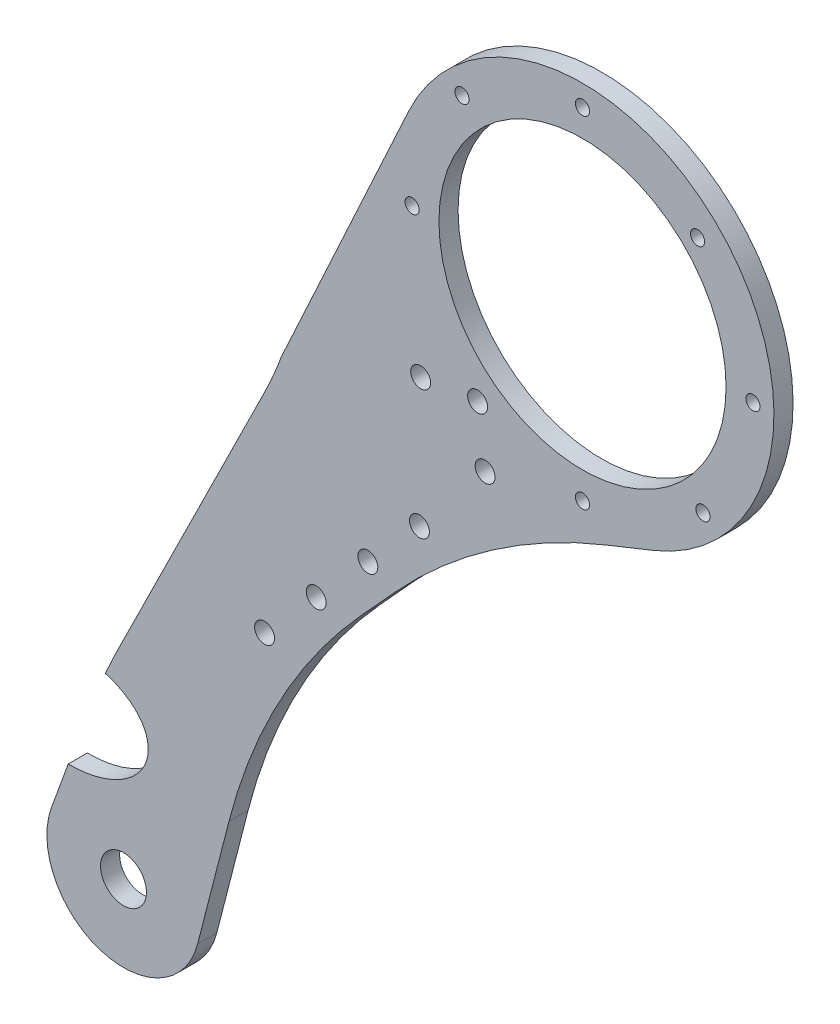
SolidWorks part; units mm, degrees
ref_plane "前视基准面" through (0, 0, 0) normal (0, 0, 1) x (1, 0, 0)
ref_plane "上视基准面" through (0, 0, 0) normal (0, 1, 0) x (1, 0, 0)
ref_plane "右视基准面" through (0, 0, 0) normal (1, 0, 0) x (0, 0, -1)
other "Configuration Table"
sketch "草图2" plane through (0, 0, 0) normal (0, 0, 1) x (1, 0, 0)
  line L3 (46.1569, 11.7262) -> (53.8034, 15.2249)
  line L4 (-24.1039, 62.5864) -> (-38.1759, 23.9239)
  line L5 (-42.531, 13.749) -> (-80.4781, -62.8808)
  line L6 (-93.8568, -96.0567) -> (-98.223, -108.0528)
  line L7 (-61.0282, -122.7294) -> (-40.8494, -75.3454)
  circle A0 centre (84.9497, 75.0973) radius 1.85
  circle A1 centre (-4.0503, 75.0973) radius 1.85
  circle A2 centre (71.916, 43.6311) radius 1.85
  circle A3 centre (-79.4291, -114.8932) radius 6
  circle A5 centre (40.4497, 30.5973) radius 1.85
  circle A7 centre (8.9835, 106.5636) radius 1.85
  circle A8 centre (40.4497, 119.5973) radius 1.85
  circle A9 centre (91.2631, 96.1449) radius 2.6
  circle A10 centre (61.4973, 125.9107) radius 2.6
  circle A11 centre (19.4021, 125.9107) radius 2.6
  circle A12 centre (-10.3636, 96.1449) radius 2.6
  circle A15 centre (61.4973, 24.284) radius 2.6
  circle A16 centre (91.2631, 54.0497) radius 2.6
  circle A21 centre (40.4497, 75.0973) radius 40
  arc A25 (-16.723, -33.5512) -> (-40.8494, -75.3454) centre (143.16, -153.707) ccw
  arc A26 (46.1569, 11.7262) -> (-16.723, -33.5512) centre (129.3708, -170.1403) ccw
  arc A27 (62.9573, 19.4789) -> (53.8034, 15.2249) centre (100.47, -73.2184) ccw
  arc A28 (62.9573, 19.4789) -> (-18.9963, 83.2315) centre (40.4497, 75.0973) ccw
  arc A29 (-24.1039, 62.5864) -> (-18.9963, 83.2315) centre (-118.0731, 96.7885) ccw
  arc A30 (-42.531, 13.749) -> (-38.1759, 23.9239) centre (-132.1451, 58.1259) ccw
  arc A31 (-80.4781, -62.8808) -> (-84.1514, -70.7209) centre (98.7501, -151.6347) ccw
  arc A32 (-98.223, -108.0528) -> (-61.0282, -122.7294) centre (-79.4291, -114.8932) ccw
  ellipse E0 centre (-92.5686, -82.8702) end of major axis (-112.1659, -83.9215) minor radius 13.1666 (-93.8568, -96.0567) -> (-84.1514, -70.7209) ccw
extrude "凸台-拉伸1" add sketch "草图2" along normal blind 5
sketch "草图4" plane through (0, 0, 5) normal (0, 0, 1) x (1, 0, 0)
  line L0 (40.4497, 75.0973) -> (13.0555, 39.3964)
  line L1 (40.4497, 75.0973) -> (40.4497, 119.5973)
  line L2 (40.4497, 75.0973) -> (13.5399, 40.0277)
  line L3 (24.9558, 30.265) -> (13.0555, 39.3964)
  line L4 (15.0134, 24.5248) -> (-1.8162, 37.4385)
  line L5 (46.1569, 11.7262) -> (53.8034, 15.2249)
  line L6 (-24.1039, 62.5864) -> (-38.1759, 23.9239)
  line L7 (-42.531, 13.749) -> (-80.4781, -62.8808)
  line L8 (-93.8568, -96.0567) -> (-98.223, -108.0528)
  line L9 (-61.0282, -122.7294) -> (-40.8494, -75.3454)
  line L10 (46.1569, 11.7262) -> (53.8034, 15.2249)
  line L11 (-24.1039, 62.5864) -> (-38.1759, 23.9239)
  line L12 (-42.531, 13.749) -> (-80.4781, -62.8808)
  line L13 (-93.8568, -96.0567) -> (-98.223, -108.0528)
  line L14 (-61.0282, -122.7294) -> (-40.8494, -75.3454)
  circle A0 centre (13.0555, 39.3964) radius 15
  circle A5 centre (15.0134, 24.5248) radius 2.6
  circle A6 centre (-1.8162, 37.4385) radius 2.6
  circle A7 centre (11.0976, 54.2681) radius 2.6
  arc A8 (46.1569, 11.7262) -> (-16.723, -33.5512) centre (129.3708, -170.1403) ccw
  arc A9 (62.9573, 19.4789) -> (53.8034, 15.2249) centre (100.47, -73.2184) ccw
  arc A10 (62.9573, 19.4789) -> (-18.9963, 83.2315) centre (40.4497, 75.0973) ccw
  arc A11 (-24.1039, 62.5864) -> (-18.9963, 83.2315) centre (-118.0731, 96.7885) ccw
  arc A12 (-42.531, 13.749) -> (-38.1759, 23.9239) centre (-132.1451, 58.1259) ccw
  arc A13 (-80.4781, -62.8808) -> (-84.1514, -70.7209) centre (98.7501, -151.6347) ccw
  arc A14 (-98.223, -108.0528) -> (-61.0282, -122.7294) centre (-79.4291, -114.8932) ccw
  arc A15 (-16.723, -33.5512) -> (-40.8494, -75.3454) centre (143.16, -153.707) ccw
  arc A16 (46.1569, 11.7262) -> (-16.723, -33.5512) centre (129.3708, -170.1403) ccw
  arc A17 (62.9573, 19.4789) -> (53.8034, 15.2249) centre (100.47, -73.2184) ccw
  arc A18 (62.9573, 19.4789) -> (-18.9963, 83.2315) centre (40.4497, 75.0973) ccw
  arc A19 (-24.1039, 62.5864) -> (-18.9963, 83.2315) centre (-118.0731, 96.7885) ccw
  arc A20 (-42.531, 13.749) -> (-38.1759, 23.9239) centre (-132.1451, 58.1259) ccw
  arc A21 (-80.4781, -62.8808) -> (-84.1514, -70.7209) centre (98.7501, -151.6347) ccw
  arc A22 (-98.223, -108.0528) -> (-61.0282, -122.7294) centre (-79.4291, -114.8932) ccw
  arc A23 (-16.723, -33.5512) -> (-40.8494, -75.3454) centre (143.16, -153.707) ccw
  circle A24 centre (27.9271, 41.3543) radius 2.6
  ellipse E1 centre (-92.5686, -82.8702) end of major axis (-72.9713, -81.819) minor radius 13.1666 (-93.8568, -96.0567) -> (-84.1514, -70.7209) ccw
  ellipse E2 centre (-92.5686, -82.8702) end of major axis (-72.9713, -81.819) minor radius 13.1666 (-93.8568, -96.0567) -> (-84.1514, -70.7209) ccw
  point P47 (13.0555, 39.3964)
  dimension "D3" = 30
  dimension "D4" = 4
  dimension "D5" = 5.2
  dimension "D6" = 142.5
  dimension "D2" = 45
  dimension "D1" = 0
extrude "切除-拉伸3" cut sketch "草图4" against normal through all contours L4 A6 A0 | A0 A6 | A0 A6 L4 | L4 A5 A0 | A0 A5 L4 | A0 A5
sketch "草图5" plane through (0, 0, 5) normal (0, 0, 1) x (1, 0, 0)
  line L0 (-8.4235, 16.054) -> (-20.1211, 24.5355)
  line L1 (-27.5368, 22.7065) -> (-60.0257, -42.901)
  line L2 (-56.7563, -45.137) -> (-7.6659, 8.6349)
  line L3 (-42.531, 13.749) -> (-80.4781, -62.8808) construction
  arc A0 (-7.6659, 8.6349) -> (-8.4235, 16.054) centre (-11.3585, 12.0061) ccw
  arc A1 (-27.5368, 22.7065) -> (-20.1211, 24.5355) centre (-23.0561, 20.4876) cw
  arc A2 (-60.0257, -42.901) -> (-56.7563, -45.137) centre (-58.2334, -43.7886) ccw
  dimension "D1" = 5
  dimension "D2" = 2
extrude "切除-拉伸4" cut sketch "草图5" against normal blind 10 contours L2 A0 L0 A1 L1 A2
sketch "草图6" plane through (0, 0, 5) normal (0, 0, 1) x (1, 0, 0)
  line L0 (40.4497, 75.0973) -> (40.4497, 119.5973)
  line L1 (40.4497, 75.0973) -> (70.5018, 105.1494)
  line L2 (40.4497, 75.0973) -> (10.3977, 45.0453)
  circle A0 centre (70.5018, 105.1494) radius 1.85
  circle A2 centre (40.4497, 75.0973) radius 40 construction
  circle A3 centre (40.4497, 75.0973) radius 40
  circle A4 centre (40.4497, 75.0973) radius 42.5
  circle A5 centre (10.3977, 45.0453) radius 1.85
  dimension "D1" = 85
  dimension "D2" = 3.7
  dimension "D4" = 3.7
  dimension "D3" = 45
extrude "切除-拉伸5" cut sketch "草图6" against normal blind 10 contours A4 A0 | A0 A4 L1 | L1 A4 A0
sketch "草图7" plane through (0, 0, 5) normal (0, 0, 1) x (1, 0, 0)
  line L0 (-38.1759, 23.9239) -> (-4.9629, 96.0183)
  line L1 (12.5033, -7.8382) -> (70.2161, 34.9232)
  line L5 (46.1569, 11.7262) -> (53.8034, 15.2249)
  line L6 (-24.1039, 62.5864) -> (-38.1759, 23.9239)
  line L7 (-42.531, 13.749) -> (-80.4781, -62.8808)
  line L8 (-93.8568, -96.0567) -> (-98.223, -108.0528)
  line L9 (-61.0282, -122.7294) -> (-40.8494, -75.3454)
  line L10 (46.1569, 11.7262) -> (53.8034, 15.2249)
  line L11 (-24.1039, 62.5864) -> (-38.1759, 23.9239)
  line L12 (-42.531, 13.749) -> (-80.4781, -62.8808)
  line L13 (-93.8568, -96.0567) -> (-98.223, -108.0528)
  line L14 (-61.0282, -122.7294) -> (-40.8494, -75.3454)
  circle A0 centre (40.4497, 75.0973) radius 40 construction
  circle A1 centre (40.4497, 75.0973) radius 40
  circle A2 centre (40.4497, 75.0973) radius 50
  arc A11 (46.1569, 11.7262) -> (-16.723, -33.5512) centre (129.3708, -170.1403) ccw
  arc A12 (62.9573, 19.4789) -> (53.8034, 15.2249) centre (100.47, -73.2184) ccw
  arc A13 (62.9573, 19.4789) -> (-18.9963, 83.2315) centre (40.4497, 75.0973) ccw
  arc A14 (-24.1039, 62.5864) -> (-18.9963, 83.2315) centre (-118.0731, 96.7885) ccw
  arc A15 (-42.531, 13.749) -> (-38.1759, 23.9239) centre (-132.1451, 58.1259) ccw
  arc A16 (-80.4781, -62.8808) -> (-84.1514, -70.7209) centre (98.7501, -151.6347) ccw
  arc A17 (-98.223, -108.0528) -> (-61.0282, -122.7294) centre (-79.4291, -114.8932) ccw
  arc A18 (-16.723, -33.5512) -> (-40.8494, -75.3454) centre (143.16, -153.707) ccw
  arc A19 (46.1569, 11.7262) -> (-16.723, -33.5512) centre (129.3708, -170.1403) ccw
  arc A20 (62.9573, 19.4789) -> (53.8034, 15.2249) centre (100.47, -73.2184) ccw
  arc A21 (62.9573, 19.4789) -> (-18.9963, 83.2315) centre (40.4497, 75.0973) ccw
  arc A22 (-24.1039, 62.5864) -> (-18.9963, 83.2315) centre (-118.0731, 96.7885) ccw
  arc A23 (-42.531, 13.749) -> (-38.1759, 23.9239) centre (-132.1451, 58.1259) ccw
  arc A24 (-80.4781, -62.8808) -> (-84.1514, -70.7209) centre (98.7501, -151.6347) ccw
  arc A25 (-98.223, -108.0528) -> (-61.0282, -122.7294) centre (-79.4291, -114.8932) ccw
  arc A26 (-16.723, -33.5512) -> (-40.8494, -75.3454) centre (143.16, -153.707) ccw
  ellipse E1 centre (-92.5686, -82.8702) end of major axis (-72.9713, -81.819) minor radius 13.1666 (-93.8568, -96.0567) -> (-84.1514, -70.7209) ccw
  ellipse E2 centre (-92.5686, -82.8702) end of major axis (-72.9713, -81.819) minor radius 13.1666 (-93.8568, -96.0567) -> (-84.1514, -70.7209) ccw
  circle M12 centre (91.2631, 54.0497) radius 2.6
  circle M14 centre (19.4021, 125.9107) radius 2.6
  circle M15 centre (91.2631, 96.1449) radius 2.6
  arc M19 (-16.723, -33.5512) -> (46.1569, 11.7262) centre (129.3708, -170.1403) cw
  line M20 (46.1569, 11.7262) -> (53.8034, 15.2249)
  arc M21 (53.8034, 15.2249) -> (62.9573, 19.4789) centre (100.47, -73.2184) cw
  arc M22 (62.9573, 19.4789) -> (-18.9963, 83.2315) centre (40.4497, 75.0973) ccw
  arc M23 (-18.9963, 83.2315) -> (-24.1039, 62.5864) centre (-118.0731, 96.7885) cw
  line M24 (-24.1039, 62.5864) -> (-38.1759, 23.9239)
  circle M37 centre (61.4973, 125.9107) radius 2.6
  circle M38 centre (-10.3636, 96.1449) radius 2.6
  circle M39 centre (61.4973, 24.284) radius 2.6
  dimension "D1" = 100
  dimension "D2" = 0
extrude "切除-拉伸6" cut sketch "草图7" against normal blind 10 contours A2 L1 L0 M19 M20 M21 M22 M23 M24 M12 M14 M37 M39 M38 M15
sketch "草图8" plane through (0, 0, 5) normal (0, 0, 1) x (1, 0, 0)
  line L3 (-27.5368, 22.7065) -> (-60.0257, -42.901)
  line L4 (-8.4235, 16.054) -> (-20.1211, 24.5355)
  line L5 (-56.7563, -45.137) -> (-7.6659, 8.6349)
  line L6 (-27.5368, 22.7065) -> (-60.0257, -42.901)
  line L7 (-8.4235, 16.054) -> (-20.1211, 24.5355)
  line L8 (-56.7563, -45.137) -> (-7.6659, 8.6349)
  line L11 (-4.9629, 96.0183) -> (-38.1759, 23.9239)
  line L12 (-42.531, 13.749) -> (-80.4781, -62.8808)
  line L13 (-93.8568, -96.0567) -> (-98.223, -108.0528)
  line L14 (-61.0282, -122.7294) -> (-40.8494, -75.3454)
  line L15 (12.5033, -7.8382) -> (70.2161, 34.9232)
  line L16 (-4.9629, 96.0183) -> (-38.1759, 23.9239)
  line L17 (-42.531, 13.749) -> (-80.4781, -62.8808)
  line L18 (-93.8568, -96.0567) -> (-98.223, -108.0528)
  line L19 (-61.0282, -122.7294) -> (-40.8494, -75.3454)
  line L20 (12.5033, -7.8382) -> (70.2161, 34.9232)
  circle A1 centre (84.9497, 75.0973) radius 1.85
  circle A2 centre (84.9497, 75.0973) radius 1.85
  circle A3 centre (-4.0503, 75.0973) radius 1.85
  circle A4 centre (-4.0503, 75.0973) radius 1.85
  circle A5 centre (71.916, 43.6311) radius 1.85
  circle A6 centre (71.916, 43.6311) radius 1.85
  circle A7 centre (-79.4291, -114.8932) radius 6
  circle A8 centre (-79.4291, -114.8932) radius 6
  circle A9 centre (40.4497, 30.5973) radius 1.85
  circle A10 centre (40.4497, 30.5973) radius 1.85
  circle A11 centre (8.9835, 106.5636) radius 1.85
  circle A12 centre (8.9835, 106.5636) radius 1.85
  circle A13 centre (40.4497, 119.5973) radius 1.85
  circle A14 centre (40.4497, 119.5973) radius 1.85
  circle A25 centre (40.4497, 75.0973) radius 40
  circle A26 centre (40.4497, 75.0973) radius 40
  circle A27 centre (15.0134, 24.5248) radius 2.6
  circle A28 centre (15.0134, 24.5248) radius 2.6
  circle A29 centre (-1.8162, 37.4385) radius 2.6
  circle A30 centre (-1.8162, 37.4385) radius 2.6
  circle A31 centre (70.5018, 105.1494) radius 1.85
  circle A32 centre (70.5018, 105.1494) radius 1.85
  arc A33 (-60.0257, -42.901) -> (-56.7563, -45.137) centre (-58.2334, -43.7886) ccw
  arc A34 (-20.1211, 24.5355) -> (-27.5368, 22.7065) centre (-23.0561, 20.4876) ccw
  arc A35 (-7.6659, 8.6349) -> (-8.4235, 16.054) centre (-11.3585, 12.0061) ccw
  arc A36 (-60.0257, -42.901) -> (-56.7563, -45.137) centre (-58.2334, -43.7886) ccw
  arc A37 (-20.1211, 24.5355) -> (-27.5368, 22.7065) centre (-23.0561, 20.4876) ccw
  arc A38 (-7.6659, 8.6349) -> (-8.4235, 16.054) centre (-11.3585, 12.0061) ccw
  arc A44 (-42.531, 13.749) -> (-38.1759, 23.9239) centre (-132.1451, 58.1259) ccw
  arc A45 (-80.4781, -62.8808) -> (-84.1514, -70.7209) centre (98.7501, -151.6347) ccw
  arc A46 (-98.223, -108.0528) -> (-61.0282, -122.7294) centre (-79.4291, -114.8932) ccw
  arc A47 (-16.723, -33.5512) -> (-40.8494, -75.3454) centre (143.16, -153.707) ccw
  arc A48 (12.5033, -7.8382) -> (-16.723, -33.5512) centre (129.3708, -170.1403) ccw
  arc A49 (70.2161, 34.9232) -> (-4.9629, 96.0183) centre (40.4497, 75.0973) ccw
  arc A50 (-42.531, 13.749) -> (-38.1759, 23.9239) centre (-132.1451, 58.1259) ccw
  arc A51 (-80.4781, -62.8808) -> (-84.1514, -70.7209) centre (98.7501, -151.6347) ccw
  arc A52 (-98.223, -108.0528) -> (-61.0282, -122.7294) centre (-79.4291, -114.8932) ccw
  arc A53 (-16.723, -33.5512) -> (-40.8494, -75.3454) centre (143.16, -153.707) ccw
  arc A54 (12.5033, -7.8382) -> (-16.723, -33.5512) centre (129.3708, -170.1403) ccw
  arc A55 (70.2161, 34.9232) -> (-4.9629, 96.0183) centre (40.4497, 75.0973) ccw
  ellipse E1 centre (-92.5686, -82.8702) end of major axis (-72.9713, -81.819) minor radius 13.1666 (-93.8568, -96.0567) -> (-84.1514, -70.7209) ccw
  ellipse E2 centre (-92.5686, -82.8702) end of major axis (-72.9713, -81.819) minor radius 13.1666 (-93.8568, -96.0567) -> (-84.1514, -70.7209) ccw
  dimension "D1" = 0
  dimension "D2" = 0
  dimension "D3" = 0
  dimension "D4" = 0
  dimension "D5" = 0
  dimension "D6" = 0
  dimension "D7" = 0
  dimension "D13" = 0
  dimension "D14" = 0
  dimension "D15" = 0
  dimension "D16" = 0
  dimension "D17" = 0
  dimension "D18" = 0
sketch "草图9" plane through (0, 0, 5) normal (0, 0, 1) x (1, 0, 0)
  circle A0 centre (40.4497, 75.0973) radius 35
  circle A1 centre (40.4497, 75.0973) radius 40 construction
  circle A2 centre (40.4497, 75.0973) radius 40
  dimension "D1" = 5
extrude "凸台-拉伸2" add sketch "草图9" against normal blind 5
sketch "草图10" plane through (0, 0, 5) normal (0, 0, 1) x (1, 0, 0)
  line L3 (-27.5368, 22.7065) -> (-60.0257, -42.901)
  line L4 (-8.4235, 16.054) -> (-20.1211, 24.5355)
  line L5 (-56.7563, -45.137) -> (-7.6659, 8.6349)
  line L6 (-27.5368, 22.7065) -> (-60.0257, -42.901)
  line L7 (-8.4235, 16.054) -> (-20.1211, 24.5355)
  line L8 (-56.7563, -45.137) -> (-7.6659, 8.6349)
  line L11 (-4.9629, 96.0183) -> (-38.1759, 23.9239)
  line L12 (-42.531, 13.749) -> (-80.4781, -62.8808)
  line L13 (-93.8568, -96.0567) -> (-98.223, -108.0528)
  line L14 (-61.0282, -122.7294) -> (-40.8494, -75.3454)
  line L15 (12.5033, -7.8382) -> (70.2161, 34.9232)
  line L16 (-4.9629, 96.0183) -> (-38.1759, 23.9239)
  line L17 (-42.531, 13.749) -> (-80.4781, -62.8808)
  line L18 (-93.8568, -96.0567) -> (-98.223, -108.0528)
  line L19 (-61.0282, -122.7294) -> (-40.8494, -75.3454)
  line L20 (12.5033, -7.8382) -> (70.2161, 34.9232)
  circle A0 centre (40.4497, 75.0973) radius 37.5
  circle A1 centre (84.9497, 75.0973) radius 1.85
  circle A2 centre (84.9497, 75.0973) radius 1.85
  circle A3 centre (-4.0503, 75.0973) radius 1.85
  circle A4 centre (-4.0503, 75.0973) radius 1.85
  circle A5 centre (71.916, 43.6311) radius 1.85
  circle A6 centre (71.916, 43.6311) radius 1.85
  circle A7 centre (-79.4291, -114.8932) radius 6
  circle A8 centre (-79.4291, -114.8932) radius 6
  circle A9 centre (40.4497, 30.5973) radius 1.85
  circle A10 centre (40.4497, 30.5973) radius 1.85
  circle A11 centre (8.9835, 106.5636) radius 1.85
  circle A12 centre (8.9835, 106.5636) radius 1.85
  circle A13 centre (40.4497, 119.5973) radius 1.85
  circle A14 centre (40.4497, 119.5973) radius 1.85
  circle A25 centre (15.0134, 24.5248) radius 2.6
  circle A26 centre (15.0134, 24.5248) radius 2.6
  circle A27 centre (-1.8162, 37.4385) radius 2.6
  circle A28 centre (-1.8162, 37.4385) radius 2.6
  circle A29 centre (70.5018, 105.1494) radius 1.85
  circle A30 centre (70.5018, 105.1494) radius 1.85
  arc A31 (-60.0257, -42.901) -> (-56.7563, -45.137) centre (-58.2334, -43.7886) ccw
  arc A32 (-20.1211, 24.5355) -> (-27.5368, 22.7065) centre (-23.0561, 20.4876) ccw
  arc A33 (-7.6659, 8.6349) -> (-8.4235, 16.054) centre (-11.3585, 12.0061) ccw
  arc A34 (-60.0257, -42.901) -> (-56.7563, -45.137) centre (-58.2334, -43.7886) ccw
  arc A35 (-20.1211, 24.5355) -> (-27.5368, 22.7065) centre (-23.0561, 20.4876) ccw
  arc A36 (-7.6659, 8.6349) -> (-8.4235, 16.054) centre (-11.3585, 12.0061) ccw
  circle A37 centre (40.4497, 75.0973) radius 35
  circle A38 centre (40.4497, 75.0973) radius 35
  arc A44 (-42.531, 13.749) -> (-38.1759, 23.9239) centre (-132.1451, 58.1259) ccw
  arc A45 (-80.4781, -62.8808) -> (-84.1514, -70.7209) centre (98.7501, -151.6347) ccw
  arc A46 (-98.223, -108.0528) -> (-61.0282, -122.7294) centre (-79.4291, -114.8932) ccw
  arc A47 (-16.723, -33.5512) -> (-40.8494, -75.3454) centre (143.16, -153.707) ccw
  arc A48 (12.5033, -7.8382) -> (-16.723, -33.5512) centre (129.3708, -170.1403) ccw
  arc A49 (70.2161, 34.9232) -> (-4.9629, 96.0183) centre (40.4497, 75.0973) ccw
  arc A50 (-42.531, 13.749) -> (-38.1759, 23.9239) centre (-132.1451, 58.1259) ccw
  arc A51 (-80.4781, -62.8808) -> (-84.1514, -70.7209) centre (98.7501, -151.6347) ccw
  arc A52 (-98.223, -108.0528) -> (-61.0282, -122.7294) centre (-79.4291, -114.8932) ccw
  arc A53 (-16.723, -33.5512) -> (-40.8494, -75.3454) centre (143.16, -153.707) ccw
  arc A54 (12.5033, -7.8382) -> (-16.723, -33.5512) centre (129.3708, -170.1403) ccw
  arc A55 (70.2161, 34.9232) -> (-4.9629, 96.0183) centre (40.4497, 75.0973) ccw
  ellipse E1 centre (-92.5686, -82.8702) end of major axis (-72.9713, -81.819) minor radius 13.1666 (-93.8568, -96.0567) -> (-84.1514, -70.7209) ccw
  ellipse E2 centre (-92.5686, -82.8702) end of major axis (-72.9713, -81.819) minor radius 13.1666 (-93.8568, -96.0567) -> (-84.1514, -70.7209) ccw
  circle M68 centre (40.4497, 75.0973) radius 35
  dimension "D19" = 75
  dimension "D1" = 0
  dimension "D2" = 0
  dimension "D3" = 0
  dimension "D4" = 0
  dimension "D5" = 0
  dimension "D6" = 0
  dimension "D7" = 0
  dimension "D13" = 0
  dimension "D14" = 0
  dimension "D15" = 0
  dimension "D16" = 0
  dimension "D17" = 0
  dimension "D18" = 0
extrude "切除-拉伸7" cut sketch "草图10" against normal blind 6 contours A0 M68
sketch "草图11" plane through (0, 0, 5) normal (0, 0, 1) x (1, 0, 0)
  line L0 (-56.7563, -45.137) -> (-7.6659, 8.6349) construction
  line L1 (-56.7563, -45.137) -> (-7.6659, 8.6349)
  line L2 (-51.2174, -50.1937) -> (-2.1269, 3.5782)
  circle A0 centre (-2.1269, 3.5782) radius 2.6
  circle A1 centre (-15.6115, -11.1923) radius 2.6
  circle A2 centre (-29.096, -25.9627) radius 2.6
  circle A3 centre (-42.5806, -40.7332) radius 2.6
  dimension "D2" = 5.2
  dimension "D4" = 20
  dimension "D1" = 7.5
  dimension "D3" = 4
extrude "切除-拉伸8" cut sketch "草图11" against normal blind 10
sketch "草图12" plane through (0, 0, 5) normal (0, 0, 1) x (1, 0, 0)
  line L3 (-27.5368, 22.7065) -> (-60.0257, -42.901)
  line L4 (-8.4235, 16.054) -> (-20.1211, 24.5355)
  line L5 (-56.7563, -45.137) -> (-7.6659, 8.6349)
  line L6 (-27.5368, 22.7065) -> (-60.0257, -42.901)
  line L7 (-8.4235, 16.054) -> (-20.1211, 24.5355)
  line L8 (-56.7563, -45.137) -> (-7.6659, 8.6349)
  line L11 (-4.9629, 96.0183) -> (-38.1759, 23.9239)
  line L12 (-42.531, 13.749) -> (-80.4781, -62.8808)
  line L13 (-93.8568, -96.0567) -> (-98.223, -108.0528)
  line L14 (-61.0282, -122.7294) -> (-40.8494, -75.3454)
  line L15 (12.5033, -7.8382) -> (70.2161, 34.9232)
  line L16 (-4.9629, 96.0183) -> (-38.1759, 23.9239)
  line L17 (-42.531, 13.749) -> (-80.4781, -62.8808)
  line L18 (-93.8568, -96.0567) -> (-98.223, -108.0528)
  line L19 (-61.0282, -122.7294) -> (-40.8494, -75.3454)
  line L20 (12.5033, -7.8382) -> (70.2161, 34.9232)
  circle A1 centre (84.9497, 75.0973) radius 1.85
  circle A2 centre (84.9497, 75.0973) radius 1.85
  circle A3 centre (-4.0503, 75.0973) radius 1.85
  circle A4 centre (-4.0503, 75.0973) radius 1.85
  circle A5 centre (71.916, 43.6311) radius 1.85
  circle A6 centre (71.916, 43.6311) radius 1.85
  circle A7 centre (-79.4291, -114.8932) radius 6
  circle A8 centre (-79.4291, -114.8932) radius 6
  circle A9 centre (40.4497, 30.5973) radius 1.85
  circle A10 centre (40.4497, 30.5973) radius 1.85
  circle A11 centre (8.9835, 106.5636) radius 1.85
  circle A12 centre (8.9835, 106.5636) radius 1.85
  circle A13 centre (40.4497, 119.5973) radius 1.85
  circle A14 centre (40.4497, 119.5973) radius 1.85
  circle A15 centre (15.0134, 24.5248) radius 2.6
  circle A16 centre (15.0134, 24.5248) radius 2.6
  circle A17 centre (-1.8162, 37.4385) radius 2.6
  circle A18 centre (-1.8162, 37.4385) radius 2.6
  circle A19 centre (70.5018, 105.1494) radius 1.85
  circle A20 centre (70.5018, 105.1494) radius 1.85
  arc A21 (-60.0257, -42.901) -> (-56.7563, -45.137) centre (-58.2334, -43.7886) ccw
  arc A22 (-20.1211, 24.5355) -> (-27.5368, 22.7065) centre (-23.0561, 20.4876) ccw
  arc A23 (-7.6659, 8.6349) -> (-8.4235, 16.054) centre (-11.3585, 12.0061) ccw
  arc A24 (-60.0257, -42.901) -> (-56.7563, -45.137) centre (-58.2334, -43.7886) ccw
  arc A25 (-20.1211, 24.5355) -> (-27.5368, 22.7065) centre (-23.0561, 20.4876) ccw
  arc A26 (-7.6659, 8.6349) -> (-8.4235, 16.054) centre (-11.3585, 12.0061) ccw
  circle A27 centre (40.4497, 75.0973) radius 37.5
  circle A28 centre (40.4497, 75.0973) radius 37.5
  circle A29 centre (-42.5806, -40.7332) radius 2.6
  circle A30 centre (-42.5806, -40.7332) radius 2.6
  circle A31 centre (-15.6115, -11.1923) radius 2.6
  circle A32 centre (-15.6115, -11.1923) radius 2.6
  circle A33 centre (-29.096, -25.9627) radius 2.6
  circle A34 centre (-29.096, -25.9627) radius 2.6
  circle A35 centre (-2.1269, 3.5782) radius 2.6
  circle A36 centre (-2.1269, 3.5782) radius 2.6
  arc A42 (-42.531, 13.749) -> (-38.1759, 23.9239) centre (-132.1451, 58.1259) ccw
  arc A43 (-80.4781, -62.8808) -> (-84.1514, -70.7209) centre (98.7501, -151.6347) ccw
  arc A44 (-98.223, -108.0528) -> (-61.0282, -122.7294) centre (-79.4291, -114.8932) ccw
  arc A45 (-16.723, -33.5512) -> (-40.8494, -75.3454) centre (143.16, -153.707) ccw
  arc A46 (12.5033, -7.8382) -> (-16.723, -33.5512) centre (129.3708, -170.1403) ccw
  arc A47 (70.2161, 34.9232) -> (-4.9629, 96.0183) centre (40.4497, 75.0973) ccw
  arc A48 (-42.531, 13.749) -> (-38.1759, 23.9239) centre (-132.1451, 58.1259) ccw
  arc A49 (-80.4781, -62.8808) -> (-84.1514, -70.7209) centre (98.7501, -151.6347) ccw
  arc A50 (-98.223, -108.0528) -> (-61.0282, -122.7294) centre (-79.4291, -114.8932) ccw
  arc A51 (-16.723, -33.5512) -> (-40.8494, -75.3454) centre (143.16, -153.707) ccw
  arc A52 (12.5033, -7.8382) -> (-16.723, -33.5512) centre (129.3708, -170.1403) ccw
  arc A53 (70.2161, 34.9232) -> (-4.9629, 96.0183) centre (40.4497, 75.0973) ccw
  ellipse E1 centre (-92.5686, -82.8702) end of major axis (-72.9713, -81.819) minor radius 13.1666 (-93.8568, -96.0567) -> (-84.1514, -70.7209) ccw
  ellipse E2 centre (-92.5686, -82.8702) end of major axis (-72.9713, -81.819) minor radius 13.1666 (-93.8568, -96.0567) -> (-84.1514, -70.7209) ccw
  dimension "D1" = 0
  dimension "D2" = 0
  dimension "D3" = 0
  dimension "D4" = 0
  dimension "D5" = 0
  dimension "D6" = 0
  dimension "D7" = 0
  dimension "D8" = 0
  dimension "D9" = 0
  dimension "D10" = 0
  dimension "D11" = 0
  dimension "D12" = 0
  dimension "D13" = 0
  dimension "D14" = 0
  dimension "D15" = 0
  dimension "D16" = 0
  dimension "D17" = 0
sketch "草图13" plane through (0, 0, 5) normal (0, 0, 1) x (1, 0, 0)
  line L0 (-1.8162, 37.4385) -> (15.0134, 24.5248)
  line L1 (6.5986, 30.9817) -> (13.0555, 39.3964)
  line L2 (13.0555, 39.3964) -> (-1.8162, 37.4385)
  line L3 (13.0555, 39.3964) -> (15.0134, 24.5248)
  circle A0 centre (15.0134, 24.5248) radius 2.6 construction
  circle A1 centre (15.0134, 24.5248) radius 2.6
  circle A2 centre (-1.8162, 37.4385) radius 2.6 construction
  circle A3 centre (-1.8162, 37.4385) radius 2.6
  circle A4 centre (13.0555, 39.3964) radius 2.6
  dimension "D2" = 5.2
  dimension "D1" = 15
extrude "切除-拉伸9" cut sketch "草图13" against normal blind 10 contours L2 A4 L1 | L1 A4 L3 | L3 A4 L2
sketch "草图14" plane through (0, 0, 5) normal (0, 0, 1) x (1, 0, 0)
  line L0 (-2.1269, 3.5782) -> (-42.5806, -40.7332)
  line L1 (-42.5806, -51.8571) -> (14.7287, 10.9175)
  line L2 (14.7287, 10.9175) -> (59.0552, 28.6879)
  line L3 (-42.5806, -51.8571) -> (-60.0585, -119.871)
  line L5 (-4.9629, 96.0183) -> (-38.1759, 23.9239)
  line L6 (-42.531, 13.749) -> (-80.4781, -62.8808)
  line L7 (-93.8568, -96.0567) -> (-98.223, -108.0528)
  line L8 (-61.0282, -122.7294) -> (-40.8494, -75.3454)
  line L9 (12.5033, -7.8382) -> (70.2161, 34.9232)
  line L10 (-4.9629, 96.0183) -> (-38.1759, 23.9239)
  line L11 (-42.531, 13.749) -> (-80.4781, -62.8808)
  line L12 (-93.8568, -96.0567) -> (-98.223, -108.0528)
  line L13 (-61.0282, -122.7294) -> (-40.8494, -75.3454)
  line L14 (12.5033, -7.8382) -> (70.2161, 34.9232)
  circle A0 centre (-42.5806, -40.7332) radius 2.6 construction
  circle A1 centre (-42.5806, -40.7332) radius 2.6
  circle A2 centre (-2.1269, 3.5782) radius 2.6 construction
  circle A3 centre (-2.1269, 3.5782) radius 2.6
  circle A4 centre (40.4497, 75.0973) radius 50
  circle A5 centre (-79.4291, -114.8932) radius 20
  arc A6 (-42.531, 13.749) -> (-38.1759, 23.9239) centre (-132.1451, 58.1259) ccw
  arc A7 (-80.4781, -62.8808) -> (-84.1514, -70.7209) centre (98.7501, -151.6347) ccw
  arc A8 (-98.223, -108.0528) -> (-61.0282, -122.7294) centre (-79.4291, -114.8932) ccw
  arc A9 (-16.723, -33.5512) -> (-40.8494, -75.3454) centre (143.16, -153.707) ccw
  arc A10 (12.5033, -7.8382) -> (-16.723, -33.5512) centre (129.3708, -170.1403) ccw
  arc A11 (70.2161, 34.9232) -> (-4.9629, 96.0183) centre (40.4497, 75.0973) ccw
  arc A12 (-42.531, 13.749) -> (-38.1759, 23.9239) centre (-132.1451, 58.1259) ccw
  arc A13 (-80.4781, -62.8808) -> (-84.1514, -70.7209) centre (98.7501, -151.6347) ccw
  arc A14 (-98.223, -108.0528) -> (-61.0282, -122.7294) centre (-79.4291, -114.8932) ccw
  arc A15 (-16.723, -33.5512) -> (-40.8494, -75.3454) centre (143.16, -153.707) ccw
  arc A16 (12.5033, -7.8382) -> (-16.723, -33.5512) centre (129.3708, -170.1403) ccw
  arc A17 (70.2161, 34.9232) -> (-4.9629, 96.0183) centre (40.4497, 75.0973) ccw
  ellipse E1 centre (-92.5686, -82.8702) end of major axis (-72.9713, -81.819) minor radius 13.1666 (-93.8568, -96.0567) -> (-84.1514, -70.7209) ccw
  ellipse E2 centre (-92.5686, -82.8702) end of major axis (-72.9713, -81.819) minor radius 13.1666 (-93.8568, -96.0567) -> (-84.1514, -70.7209) ccw
  line M30 (-61.0282, -122.7294) -> (-40.8494, -75.3454)
  arc M31 (-40.8494, -75.3454) -> (-16.723, -33.5512) centre (143.16, -153.707) cw
  arc M32 (-16.723, -33.5512) -> (12.5033, -7.8382) centre (129.3708, -170.1403) cw
  line M33 (12.5033, -7.8382) -> (70.2161, 34.9232)
  dimension "D2" = 85
  dimension "D3" = 7.5
  dimension "D1" = 0
extrude "切除-拉伸10" cut sketch "草图14" against normal blind 10 contours A5 A4 L2 L1 L3 M30 M31 M32 M33
fillet "圆角1" radius 150 2 edges at (-42.5806, -51.8571, 2.5) (14.7287, 10.9175, 2.5)
sketch "草图15" plane through (0, 0, 5) normal (0, 0, 1) x (1, 0, 0)
  line L3 (-27.5368, 22.7065) -> (-60.0257, -42.901)
  line L4 (-8.4235, 16.054) -> (-20.1211, 24.5355)
  line L5 (-56.7563, -45.137) -> (-7.6659, 8.6349)
  line L6 (-27.5368, 22.7065) -> (-60.0257, -42.901)
  line L7 (-8.4235, 16.054) -> (-20.1211, 24.5355)
  line L8 (-56.7563, -45.137) -> (-7.6659, 8.6349)
  circle A1 centre (84.9497, 75.0973) radius 1.85
  circle A2 centre (84.9497, 75.0973) radius 1.85
  circle A3 centre (-4.0503, 75.0973) radius 1.85
  circle A4 centre (-4.0503, 75.0973) radius 1.85
  circle A5 centre (-79.4291, -114.8932) radius 6
  circle A6 centre (-79.4291, -114.8932) radius 6
  circle A7 centre (8.9835, 106.5636) radius 1.85
  circle A8 centre (8.9835, 106.5636) radius 1.85
  circle A9 centre (71.916, 43.6311) radius 1.85
  circle A10 centre (71.916, 43.6311) radius 1.85
  circle A11 centre (40.4497, 30.5973) radius 1.85
  circle A12 centre (40.4497, 30.5973) radius 1.85
  circle A13 centre (40.4497, 119.5973) radius 1.85
  circle A14 centre (40.4497, 119.5973) radius 1.85
  circle A15 centre (15.0134, 24.5248) radius 2.6
  circle A16 centre (15.0134, 24.5248) radius 2.6
  circle A17 centre (-1.8162, 37.4385) radius 2.6
  circle A18 centre (-1.8162, 37.4385) radius 2.6
  circle A19 centre (70.5018, 105.1494) radius 1.85
  circle A20 centre (70.5018, 105.1494) radius 1.85
  arc A21 (-60.0257, -42.901) -> (-56.7563, -45.137) centre (-58.2334, -43.7886) ccw
  arc A22 (-20.1211, 24.5355) -> (-27.5368, 22.7065) centre (-23.0561, 20.4876) ccw
  arc A23 (-7.6659, 8.6349) -> (-8.4235, 16.054) centre (-11.3585, 12.0061) ccw
  arc A24 (-60.0257, -42.901) -> (-56.7563, -45.137) centre (-58.2334, -43.7886) ccw
  arc A25 (-20.1211, 24.5355) -> (-27.5368, 22.7065) centre (-23.0561, 20.4876) ccw
  arc A26 (-7.6659, 8.6349) -> (-8.4235, 16.054) centre (-11.3585, 12.0061) ccw
  circle A27 centre (-42.5806, -40.7332) radius 2.6
  circle A28 centre (-42.5806, -40.7332) radius 2.6
  circle A29 centre (40.4497, 75.0973) radius 37.5
  circle A30 centre (40.4497, 75.0973) radius 37.5
  circle A31 centre (-15.6115, -11.1923) radius 2.6
  circle A32 centre (-15.6115, -11.1923) radius 2.6
  circle A33 centre (-29.096, -25.9627) radius 2.6
  circle A34 centre (-29.096, -25.9627) radius 2.6
  circle A35 centre (-2.1269, 3.5782) radius 2.6
  circle A36 centre (-2.1269, 3.5782) radius 2.6
  circle A37 centre (13.0555, 39.3964) radius 2.6
  circle A38 centre (13.0555, 39.3964) radius 2.6
  dimension "D1" = 0
  dimension "D2" = 0
  dimension "D3" = 0
  dimension "D4" = 0
  dimension "D5" = 0
  dimension "D6" = 0
  dimension "D7" = 0
  dimension "D8" = 0
  dimension "D9" = 0
  dimension "D10" = 0
  dimension "D11" = 0
  dimension "D12" = 0
  dimension "D13" = 0
  dimension "D14" = 0
  dimension "D15" = 0
  dimension "D16" = 0
  dimension "D17" = 0
extrude "凸台-拉伸3" add sketch "草图15" against normal through all contours A24 L8 A26 L7 A25 L6
move or copy body "实体-移动/复制1" [suppressed] bodies to move or copy 126 parameters "D1"=0, "D2"=0, "D3"=0
move or copy body "实体-移动/复制2" [suppressed] bodies to move or copy 127 parameters "D1"=0, "D2"=0, "D3"=0
